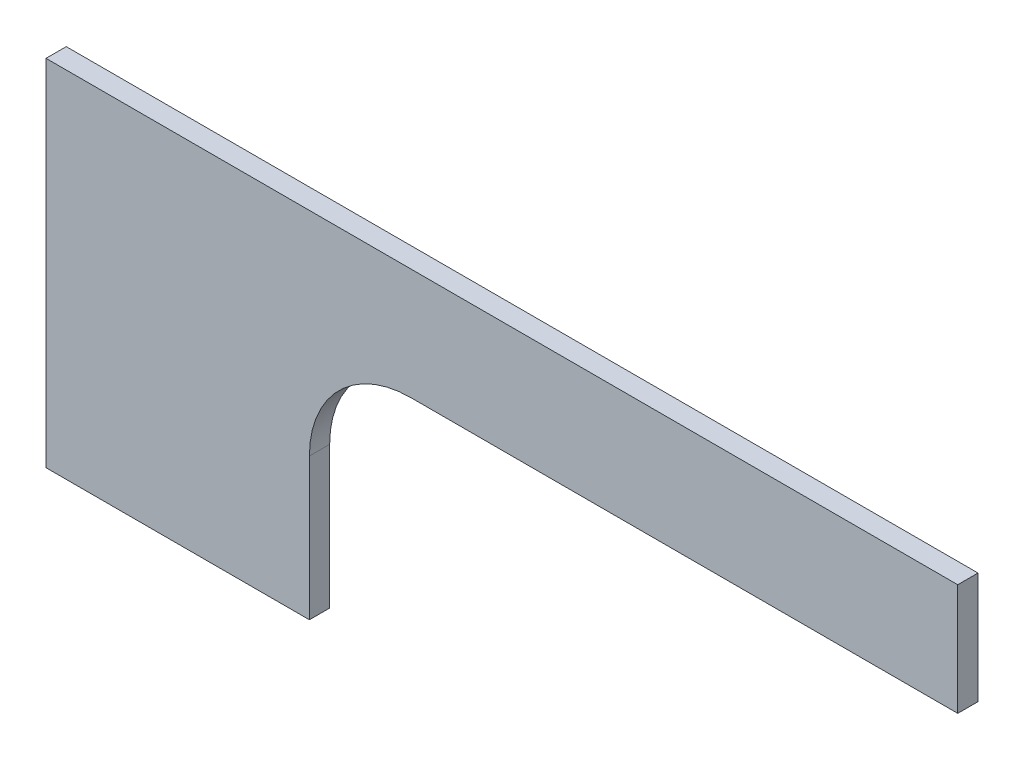
SolidWorks part; units mm, degrees
material "Galvanized Steel"
ref_plane "Front Plane" through (0, 0, 0) normal (0, 0, 1) x (1, 0, 0)
ref_plane "Top Plane" through (0, 0, 0) normal (0, 1, 0) x (1, 0, 0)
ref_plane "Right Plane" through (0, 0, 0) normal (1, 0, 0) x (0, 0, -1)
sketch "Sketch1" plane through (0, 0, 0) normal (0, 0, 1) x (1, 0, 0)
  line L0 (-18.2089, -17.1923) -> (-18.2089, 6.8077)
  line L1 (-44.2089, -17.1923) -> (-18.2089, -17.1923)
  line L2 (-44.2089, -17.1923) -> (-44.2089, 17.8077)
  line L3 (-44.2089, 17.8077) -> (45.7911, 17.8077)
  line L4 (45.7911, 6.8077) -> (45.7911, 17.8077)
  line L5 (-44.2089, -17.1923) -> (45.7911, 17.8077) construction
  line L6 (-44.2089, 17.8077) -> (43.7887, -17.6384) construction
  line L7 (-18.2089, 6.8077) -> (45.7911, 6.8077)
  point P0 (0, 0)
  dimension "D1" = 90
  dimension "D2" = 35
  dimension "D3" = 11
  dimension "D4" = 26
extrude "Boss-Extrude1" add sketch "Sketch1" along normal blind 2
fillet "Fillet2" radius 10 1 edges at (-18.2089, 6.8077, 1)
